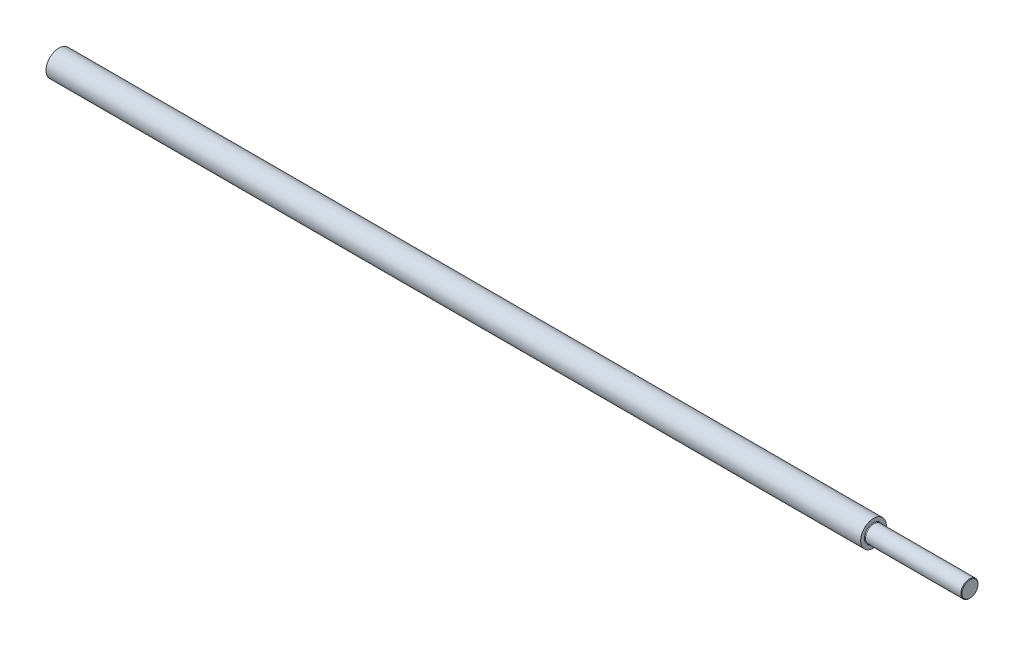
SolidWorks part; units mm, degrees
ref_plane "Front Plane" through (0, 0, 0) normal (0, 0, 1) x (1, 0, 0)
ref_plane "Top Plane" through (0, 0, 0) normal (0, 1, 0) x (1, 0, 0)
ref_plane "Right Plane" through (0, 0, 0) normal (1, 0, 0) x (0, 0, -1)
ref_plane "Plane1" through (0, 0, 0) normal (0, 0, 1) x (1, 0, 0)
sketch "Sketch1" plane through (0, 0, 0) normal (0, 0, 1) x (1, 0, 0)
  line L0 (0, 0) -> (0, 6)
  line L1 (0, 6) -> (380, 6)
  line L2 (380, 6) -> (380, 4.3)
  line L3 (380.3, 4) -> (424.7333, 4)
  line L4 (424.7333, 4) -> (425, 3.7333)
  line L5 (425, 3.7333) -> (425, 0)
  line L6 (425, 0) -> (0, 0)
  line L7 (425, 0) -> (0, 0) construction
  arc A0 (380, 4.3) -> (380.3, 4) centre (380.3, 4.3) ccw
  dimension "D7" = 0.3
  dimension "D1" = 425
  dimension "D2" = 45
  dimension "D3" = 6
  dimension "D4" = 4
  dimension "D5" = 0.2667
  dimension "D6" = 135
revolve "Revolve1" add sketch "Sketch1" angle 360 about L7
cosmetic thread "Cosmetic Thread1" parameters "D1"=370, "D2"=9.5
